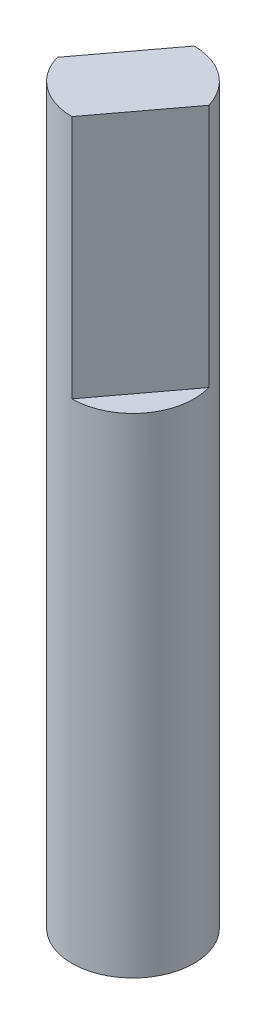
SolidWorks part; units mm, degrees
ref_plane "Front Plane" through (0, 0, 0) normal (0, 0, 1) x (1, 0, 0)
ref_plane "Top Plane" through (0, 0, 0) normal (0, 1, 0) x (1, 0, 0)
ref_plane "Right Plane" through (0, 0, 0) normal (1, 0, 0) x (0, 0, -1)
sketch "Sketch1" plane through (0, 0, 0) normal (0, 1, 0) x (1, 0, 0)
  circle A0 centre (0, 0) radius 2.5
  dimension "D1" = 5
extrude "Boss-Extrude1" add sketch "Sketch1" along normal blind 30
sketch "Sketch2" plane through (0, 30, 0) normal (0, 1, 0) x (1, 0, 0)
  line L0 (0, 2.5) -> (-2.4, -0.7)
  line L3 (0, -2.5) -> (2.4, 0.7)
  circle A0 centre (0, 0) radius 2.5 construction
  arc A1 (0, -2.5) -> (2.4, 0.7) centre (0, 0) ccw
  arc A2 (0, 2.5) -> (-2.4, -0.7) centre (0, 0) ccw
  dimension "D1" = 4
extrude "Cut-Extrude1" cut sketch "Sketch2" against normal blind 10
